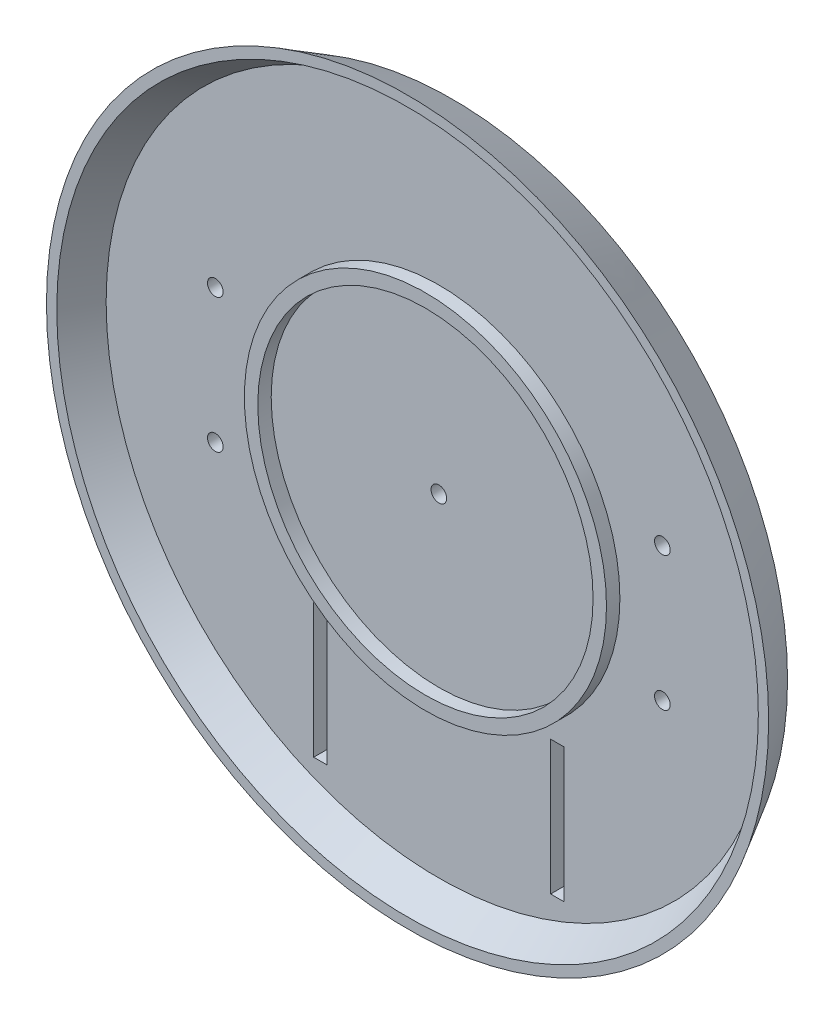
SolidWorks part; units mm, degrees
ref_plane "Front Plane" through (0, 0, 0) normal (0, 0, 1) x (1, 0, 0)
ref_plane "Top Plane" through (0, 0, 0) normal (0, 1, 0) x (1, 0, 0)
ref_plane "Right Plane" through (0, 0, 0) normal (1, 0, 0) x (0, 0, -1)
sketch "Sketch1" plane through (0, 0, 0) normal (0, 0, 1) x (1, 0, 0)
  circle A0 centre (0, 0) radius 75
  dimension "D1" = 150
extrude "Boss-Extrude1" add sketch "Sketch1" along normal blind 3
sketch "Sketch2" plane through (0, 0, 3) normal (0, 0, 1) x (1, 0, 0)
  line L1 (-50, 15) -> (50, 15) construction
  line L2 (-50, 15) -> (-50, -15) construction
  line L3 (-50, -15) -> (50, -15) construction
  line L4 (50, 15) -> (50, -15) construction
  line L5 (-50, 15) -> (50, -15) construction
  line L6 (-50, -15) -> (50, 15) construction
  circle A0 centre (-50, 15) radius 1.75
  circle A1 centre (-50, -15) radius 1.75
  circle A2 centre (50, -15) radius 1.75
  circle A3 centre (50, 15) radius 1.75
  circle A4 centre (0, 0) radius 1.75
  point P0 (0, 0)
  dimension "D3" = 3.5
  dimension "D1" = 100
  dimension "D2" = 30
extrude "Cut-Extrude1" cut sketch "Sketch2" against normal through all
sketch "Sketch3" plane through (0, 0, 3) normal (0, 0, 1) x (1, 0, 0)
  circle A0 centre (0, 0) radius 37.5
  circle A1 centre (0, 0) radius 40.5
  dimension "D1" = 75
  dimension "D2" = 3
extrude "Boss-Extrude2" add sketch "Sketch3" along normal blind 3
sketch "Sketch4" plane through (0, 0, 0) normal (0, 0, -1) x (-1, 0, 0)
  line L0 (0, -50) -> (0, 0) construction
  line L1 (-25, -35) -> (25, -35) construction
  line L2 (-25, -35) -> (-25, -65)
  line L3 (-25, -65) -> (25, -65) construction
  line L4 (25, -35) -> (25, -65)
  line L5 (-25, -35) -> (25, -65) construction
  line L6 (-25, -65) -> (25, -35) construction
  line L8 (25, -35) -> (28, -35)
  line L9 (25, -35) -> (25, -65)
  line L10 (25, -65) -> (28, -65)
  line L11 (28, -35) -> (28, -65)
  line L12 (-25, -35) -> (-28, -35)
  line L13 (-25, -35) -> (-25, -65)
  line L14 (-25, -65) -> (-28, -65)
  line L15 (-28, -35) -> (-28, -65)
  point P0 (0, -50)
  dimension "D1" = 3
  dimension "D2" = 50
  dimension "D3" = 30
  dimension "D4" = 35
extrude "Cut-Extrude2" cut sketch "Sketch4" against normal through all contours L12 L15 L14 L2 | L11 L8 L4 L10
sketch "Sketch5" plane through (0, 0, 0) normal (0, 1, 0) x (1, 0, 0)
  line L0 (-75, 0) -> (-80.7735, -10)
  line L1 (-80.7735, -10) -> (-78.4641, -10)
  line L2 (-78.4641, -10) -> (-72.6906, 0)
  line L3 (-72.6906, 0) -> (-75, 0)
  line L4 (75, 0) -> (-75, 0) construction
  line L5 (0, 0) -> (0, -22.4281) construction
  dimension "D1" = 2
  dimension "D2" = 60
  dimension "D3" = 10
revolve "Revolve1" add sketch "Sketch5" angle 360 about L5
